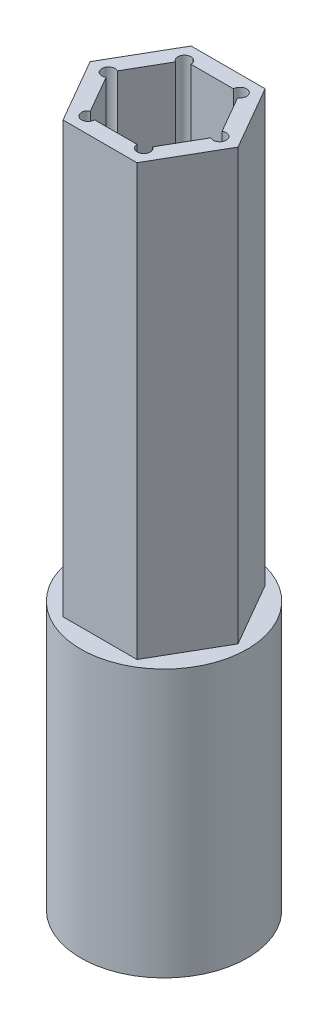
SolidWorks part; units mm, degrees
ref_plane "Front Plane" through (0, 0, 0) normal (0, 0, 1) x (1, 0, 0)
ref_plane "Top Plane" through (0, 0, 0) normal (0, 1, 0) x (1, 0, 0)
ref_plane "Right Plane" through (0, 0, 0) normal (1, 0, 0) x (0, 0, -1)
sketch "Sketch1" plane through (0, 0, 0) normal (0, 1, 0) x (1, 0, 0)
  line L1 (2.9734, 0) -> (1.4867, 2.575)
  line L2 (1.4867, 2.575) -> (-1.4867, 2.575)
  line L3 (-1.4867, 2.575) -> (-2.9734, 0)
  line L4 (-2.9734, 0) -> (-1.4867, -2.575)
  line L5 (-1.4867, -2.575) -> (1.4867, -2.575)
  line L6 (1.4867, -2.575) -> (2.9734, 0)
  line L7 (1.9774, 3.425) -> (-1.9774, 3.425)
  line L8 (-1.9774, 3.425) -> (-3.9548, 0)
  line L9 (-3.9548, 0) -> (-1.9774, -3.425)
  line L10 (-1.9774, -3.425) -> (1.9774, -3.425)
  line L11 (1.9774, -3.425) -> (3.9548, 0)
  line L12 (3.9548, 0) -> (1.9774, 3.425)
  circle A0 centre (0, 0) radius 2.575 construction
  circle A1 centre (0, 0) radius 3.425 construction
  dimension "D1" = 5.15
  dimension "D2" = 6.85
extrude "Boss-Extrude1" add sketch "Sketch1" along normal blind 23
sketch "Sketch2" plane through (0, 0, 0) normal (0, -1, 0) x (1, 0, 0)
  line L6 (2.9734, 0) -> (1.4867, 2.575)
  line L7 (1.4867, -2.575) -> (2.9734, 0)
  line L8 (-1.4867, -2.575) -> (1.4867, -2.575)
  line L9 (-2.9734, 0) -> (-1.4867, -2.575)
  line L10 (-1.4867, 2.575) -> (-2.9734, 0)
  line L11 (1.4867, 2.575) -> (-1.4867, 2.575)
  line L12 (2.9734, 0) -> (1.4867, 2.575)
  line L13 (1.4867, -2.575) -> (2.9734, 0)
  line L14 (-1.4867, -2.575) -> (1.4867, -2.575)
  line L15 (-2.9734, 0) -> (-1.4867, -2.575)
  line L16 (-1.4867, 2.575) -> (-2.9734, 0)
  line L17 (1.4867, 2.575) -> (-1.4867, 2.575)
  circle A0 centre (0, 0) radius 4.45
  dimension "D2" = 8.9
  dimension "D1" = 0
extrude "Boss-Extrude2" add sketch "Sketch2" along normal blind 14.3
sketch "Sketch4" plane through (0, 23, 0) normal (0, 1, 0) x (1, 0, 0)
  circle A0 centre (1.4867, 2.575) radius 0.35
  circle A1 centre (2.9734, 0) radius 0.35
  circle A2 centre (1.4867, -2.575) radius 0.35
  circle A3 centre (-1.4867, -2.575) radius 0.35
  circle A4 centre (-2.9734, 0) radius 0.35
  circle A5 centre (-1.4867, 2.575) radius 0.35
  point P16 (0, 0)
  dimension "D2" = 0.7
  dimension "D1" = 6
extrude "Cut-Extrude1" cut sketch "Sketch4" against normal through all both and the other way through all
